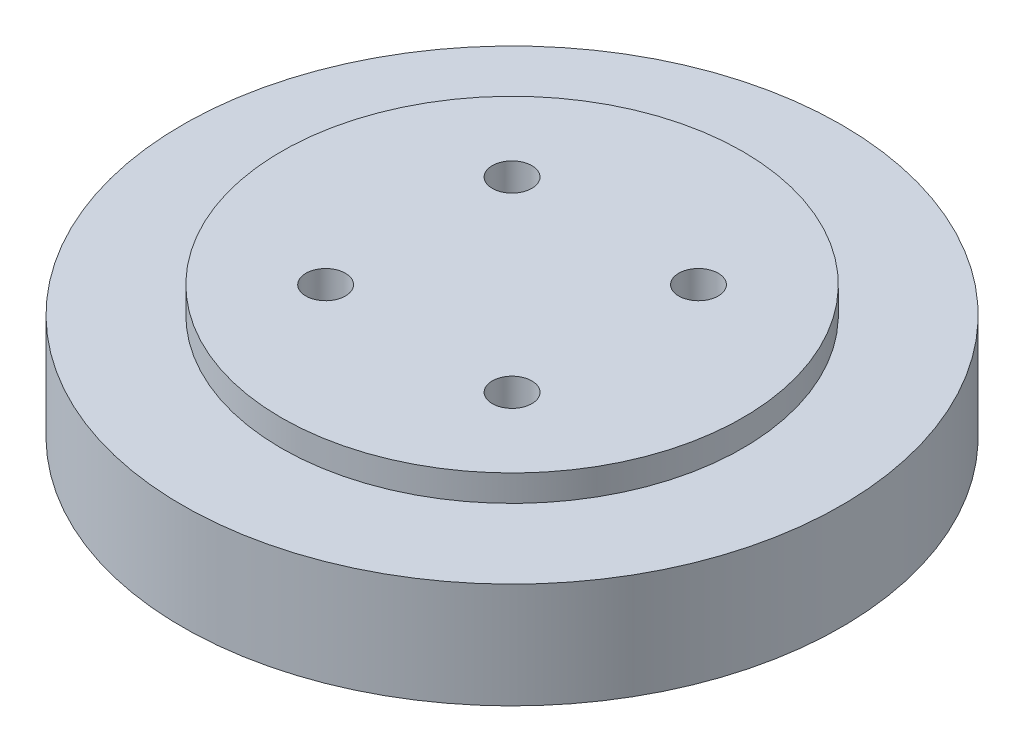
SolidWorks part; units mm, degrees
material "Titanium Ti-8Mn, Annealed"
ref_plane "Front Plane" through (0, 0, 0) normal (0, 0, 1) x (1, 0, 0)
ref_plane "Top Plane" through (0, 0, 0) normal (0, 1, 0) x (1, 0, 0)
ref_plane "Right Plane" through (0, 0, 0) normal (1, 0, 0) x (0, 0, -1)
sketch "Sketch2" plane through (0, 0, 0) normal (0, 0, 1) x (1, 0, 0)
  line L0 (0, 0) -> (0, 25.1811) construction
  line L1 (0, 0) -> (7, 0)
  line L2 (7, 0) -> (7, 7)
  line L3 (7, 7) -> (24, 7)
  line L4 (24, 7) -> (24, 0)
  line L5 (24, 0) -> (25, 0)
  line L6 (25, 0) -> (25, 8)
  line L7 (25, 8) -> (17.5, 8)
  line L8 (17.5, 8) -> (17.5, 10)
  line L9 (17.5, 10) -> (0, 10)
  line L10 (0, 10) -> (0, 0)
  dimension "D1" = 50
  dimension "D2" = 35
  dimension "D3" = 10
  dimension "D4" = 1
  dimension "D5" = 1
  dimension "D6" = 3
  dimension "D7" = 7
revolve "Revolve1" add sketch "Sketch2" angle 360 about L0
sketch "Sketch3" plane through (0, 10, 0) normal (0, 1, 0) x (1, 0, 0)
  line L0 (0, 0) -> (-7.0711, 7.0711) construction
  line L1 (0, 0) -> (-10, 0) construction
  circle A0 centre (0, 0) radius 10 construction
  circle A1 centre (-7.0711, 7.0711) radius 1.5
  dimension "D1" = 20
  dimension "D3" = 3
  dimension "D2" = 45
extrude "Cut-Extrude1" cut sketch "Sketch3" against normal through all contours A1
pattern_circular "CirPattern1" count 4 over 360 about axis through (0, 0, 0) along (0, 1, 0) of "Cut-Extrude1"
sketch "Sketch4" plane through (0, 0, 0) normal (0, -1, 0) x (1, 0, 0)
  line L0 (0, 0) -> (0, 7) construction
  line L1 (-1.2155, 6.8937) -> (-1.0419, 5.9088)
  line L2 (1.2155, 6.8937) -> (1.0419, 5.9088)
  arc A0 (1.0419, 5.9088) -> (-1.0419, 5.9088) centre (0, 0) ccw
  circle A1 centre (0, 0) radius 7
  arc A2 (1.2155, 6.8937) -> (-1.2155, 6.8937) centre (0, 0) ccw
  circle A3 centre (0, 0) radius 7 construction
  circle A4 centre (0, 0) radius 6 construction
  dimension "D3" = 10
  dimension "D1" = 0
  dimension "D2" = 1
extrude "Cut-Extrude2" cut sketch "Sketch4" against normal up to surface (7 mm away) up to face at (-7.0711, 7, 5.5711)
pattern_circular "CirPattern2" count 6 over 360 about axis through (0, 0, 0) along (0, 1, 0) of "Cut-Extrude2"
